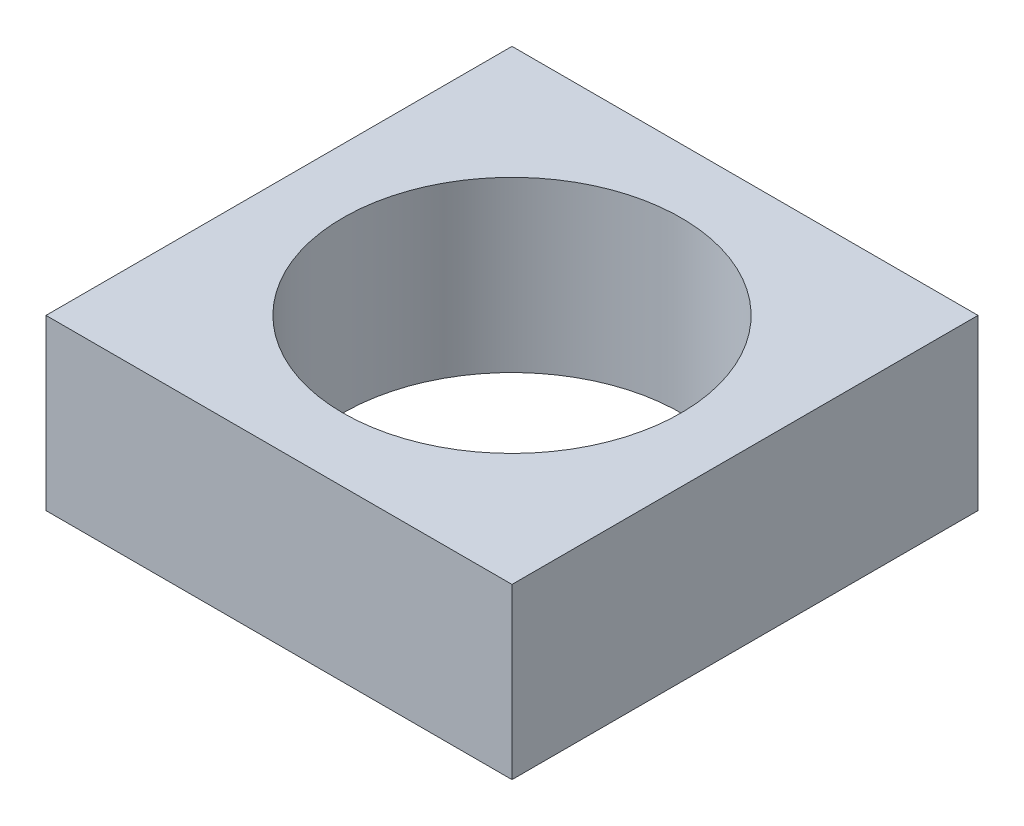
SolidWorks part; units mm, degrees
material "AISI 1020"
ref_plane "Front Plane" through (0, 0, 0) normal (0, 0, 1) x (1, 0, 0)
ref_plane "Top Plane" through (0, 0, 0) normal (0, 1, 0) x (1, 0, 0)
ref_plane "Right Plane" through (0, 0, 0) normal (1, 0, 0) x (0, 0, -1)
sketch "Sketch1" plane through (0, 0, 0) normal (0, 1, 0) x (1, 0, 0)
  line L1 (-17.5, -17.5) -> (17.5, -17.5)
  line L2 (-17.5, -17.5) -> (-17.5, 17.5)
  line L3 (-17.5, 17.5) -> (17.5, 17.5)
  line L4 (17.5, -17.5) -> (17.5, 17.5)
  line L5 (-17.5, -17.5) -> (17.5, 17.5) construction
  line L6 (-17.5, 17.5) -> (17.5, -17.5) construction
  circle A0 centre (0, 0) radius 12.7
  dimension "D1" = 35
  dimension "D3" = 25.4
  dimension "D2" = 35
extrude "Boss-Extrude1" add sketch "Sketch1" along normal blind 12.7
